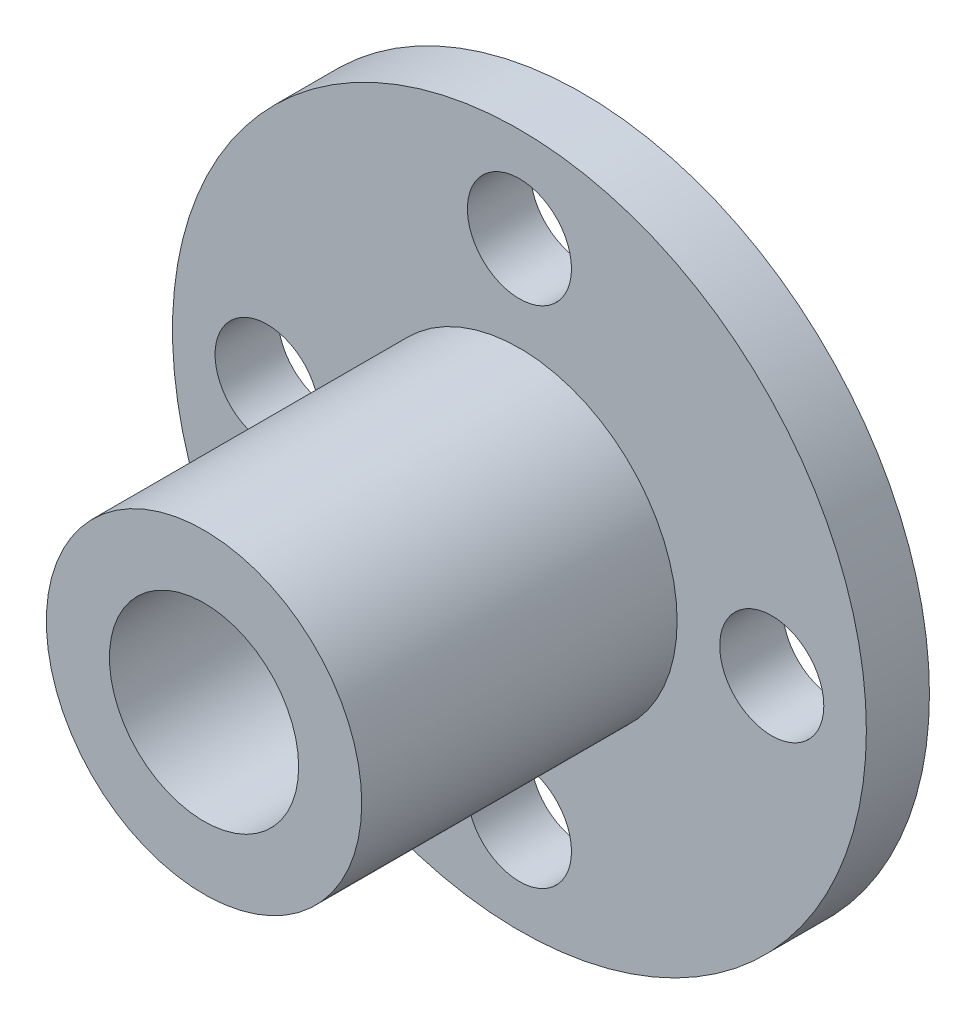
SolidWorks part; units mm, degrees
ref_plane "前视基准面" through (0, 0, 0) normal (0, 0, 1) x (1, 0, 0)
ref_plane "上视基准面" through (0, 0, 0) normal (0, 1, 0) x (1, 0, 0)
ref_plane "右视基准面" through (0, 0, 0) normal (1, 0, 0) x (0, 0, -1)
sketch "草图1" plane through (0, 0, 0) normal (0, 0, 1) x (1, 0, 0)
  circle A0 centre (0, 0) radius 11
  circle A1 centre (0, 0) radius 3
  circle A2 centre (0, 8) radius 1.65
  circle A3 centre (8, 0) radius 1.65
  circle A4 centre (0, -8) radius 1.65
  circle A5 centre (-8, 0) radius 1.65
  dimension "D1" = 22
  dimension "D2" = 6
  dimension "D3" = 3.3
  dimension "D4" = 3.3
  dimension "D5" = 3.3
  dimension "D6" = 3.3
  dimension "D7" = 8
  dimension "D8" = 8
  dimension "D9" = 8
  dimension "D10" = 8
extrude "凸台-拉伸1" add sketch "草图1" along normal blind 2
sketch "草图2" plane through (0, 0, 2) normal (0, 0, 1) x (1, 0, 0)
  circle A0 centre (0, 0) radius 5
  circle A1 centre (0, 0) radius 3 construction
  circle A2 centre (0, 0) radius 3
  dimension "D1" = 10
extrude "凸台-拉伸2" add sketch "草图2" along normal blind 10
